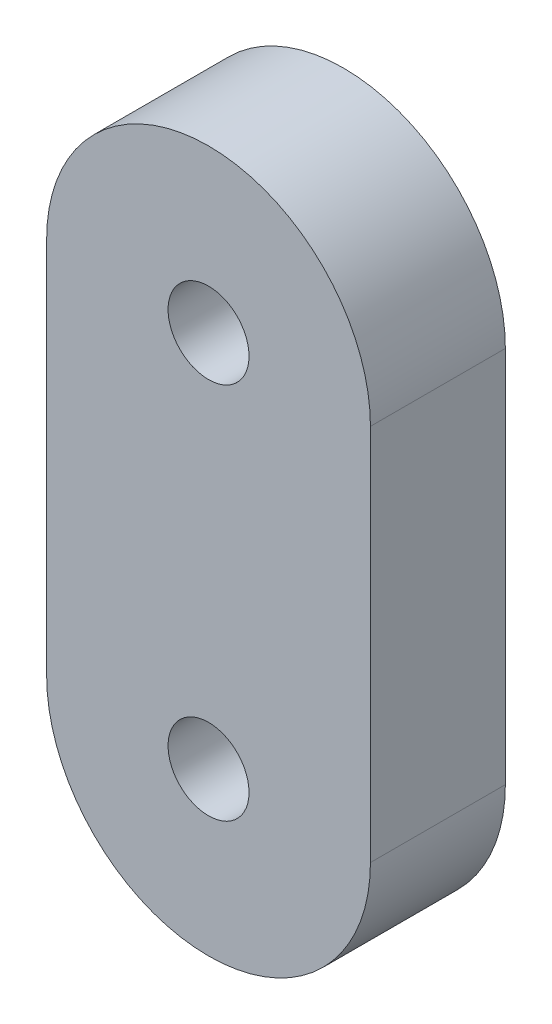
SolidWorks part; units mm, degrees
ref_plane "Front Plane" through (0, 0, 0) normal (0, 0, 1) x (1, 0, 0)
ref_plane "Top Plane" through (0, 0, 0) normal (0, 1, 0) x (1, 0, 0)
ref_plane "Right Plane" through (0, 0, 0) normal (1, 0, 0) x (0, 0, -1)
sketch "Sketch1" plane through (0, 0, 0) normal (0, 0, 1) x (1, 0, 0)
  line L0 (0, 0) -> (0, 14) construction
  line L1 (-6, 0) -> (-6, 14)
  line L2 (6, 0) -> (6, 14)
  arc A0 (-6, 0) -> (6, 0) centre (0, 0) ccw
  arc A1 (6, 14) -> (-6, 14) centre (0, 14) ccw
  circle A2 centre (0, 0) radius 1.5
  circle A3 centre (0, 14) radius 1.5
  point P3 (0, 7)
  dimension "D1" = 3
  dimension "D2" = 6
  dimension "D3" = 14
extrude "Boss-Extrude1" add sketch "Sketch1" along normal blind 5
